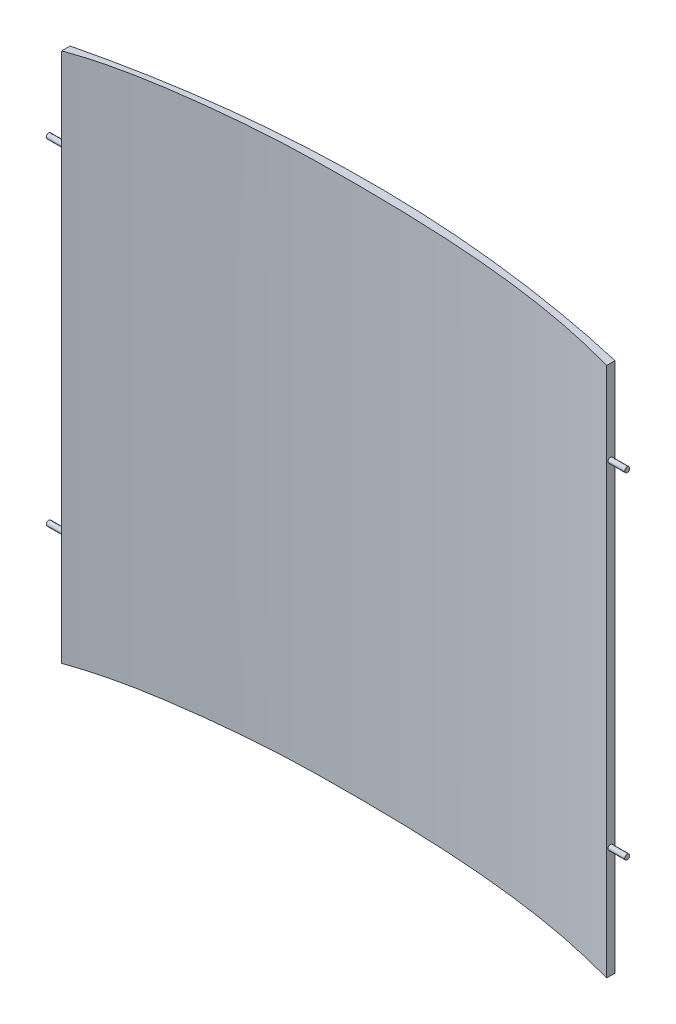
SolidWorks part; units mm, degrees
ref_plane "Front Plane" through (0, 0, 0) normal (0, 0, 1) x (1, 0, 0)
ref_plane "Top Plane" through (0, 0, 0) normal (0, 1, 0) x (1, 0, 0)
ref_plane "Right Plane" through (0, 0, 0) normal (1, 0, 0) x (0, 0, -1)
sketch "Sketch1" plane through (0, 0, 0) normal (0, 0, 1) x (1, 0, 0)
  line L1 (-325, -316.3704) -> (325, -316.3704)
  line L2 (-325, -316.3704) -> (-325, 316.3704)
  line L3 (-325, 316.3704) -> (325, 316.3704)
  line L4 (325, -316.3704) -> (325, 316.3704)
  line L5 (-325, -316.3704) -> (325, 316.3704) construction
  line L6 (-325, 316.3704) -> (325, -316.3704) construction
  point P0 (0, 0)
  dimension "D1" = 632.7408
  dimension "D2" = 650
extrude "Boss-Extrude1" add sketch "Sketch1" along normal blind 100
sketch "Sketch2" plane through (0, 316.3704, 0) normal (0, 1, 0) x (1, 0, 0)
  line L0 (-325, -100) -> (-325, 0) construction
  line L1 (325, -100) -> (325, 0) construction
  line L4 (-325, -50) -> (-325, 0)
  line L5 (-325, 0) -> (325, 0)
  line L6 (325, 0) -> (325, -50)
  line L7 (-325, -60.0019) -> (-325, -100)
  line L8 (-325, -100) -> (325, -100)
  line L9 (325, -100) -> (325, -60.0019)
  spline S0 degree 2 poles (-325, -50) (-8.1615, 26.4039) (325, -50) knots 0 0 0 1 1 1
  spline S1 degree 3 poles (-325, -60.0019) (-285.7202, -45.9173) (-211.5513, -32.9619) (-108.2864, -22.7976) (68.9455, -20.4642) (213.0376, -28.3716) (325, -60.0019) knots 0 0 0 0 0.190277 0.342513 0.47409 1 1 1 1
extrude "Cut-Extrude1" cut sketch "Sketch2" against normal blind 727
sketch "Sketch3" plane through (325, 0, 0) normal (1, 0, 0) x (0, 0, -1)
  line L0 (-60.0019, 316.3704) -> (-50, 316.3704) construction
  circle A0 centre (-55.4616, 216.3704) radius 3
  circle A1 centre (-55.4616, -183.6296) radius 3
  dimension "D1" = 6
  dimension "D2" = 6
  dimension "D3" = 100
  dimension "D4" = 400
extrude "Boss-Extrude2" add sketch "Sketch3" along normal blind 20
mirror "Mirror1" about plane through (0, 0, 0) normal (1, 0, 0) of "Boss-Extrude2"
